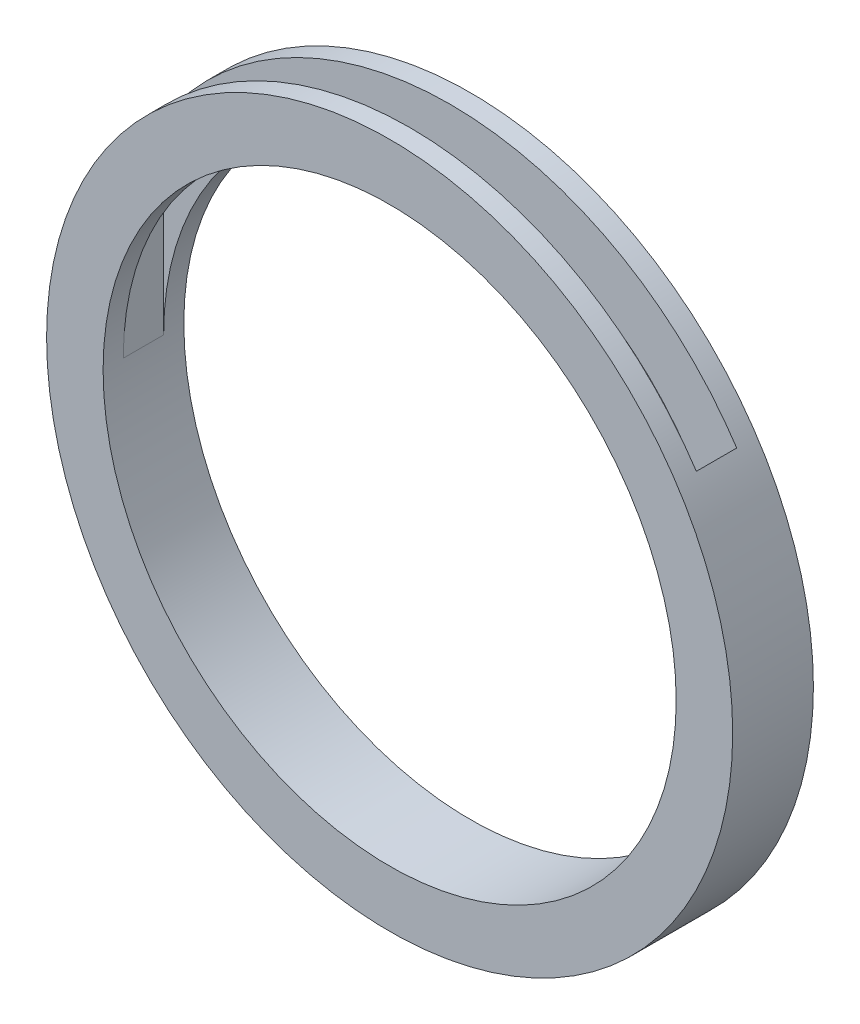
SolidWorks part; units mm, degrees
ref_plane "Front Plane" through (0, 0, 0) normal (0, 0, 1) x (1, 0, 0)
ref_plane "Top Plane" through (0, 0, 0) normal (0, 1, 0) x (1, 0, 0)
ref_plane "Right Plane" through (0, 0, 0) normal (1, 0, 0) x (0, 0, -1)
sketch "Sketch1" plane through (0, 0, 0) normal (0, 0, 1) x (1, 0, 0)
  circle A0 centre (0, 0) radius 21.59
  dimension "D1" = 43.18
extrude "Boss-Extrude1" add sketch "Sketch1" along normal blind 5.08
sketch "Sketch4" plane through (0, 0, 5.08) normal (0, 0, 1) x (1, 0, 0)
  circle A0 centre (0, 0) radius 18.034
  dimension "D1" = 36.068
extrude "Cut-Extrude1" cut sketch "Sketch4" against normal through all
sketch "Sketch5" plane through (0, 0, 0) normal (0, 1, 0) x (1, 0, 0)
  line L0 (-21.59, -2.54) -> (0, -2.54) construction
  line L1 (-21.59, 0) -> (-21.59, -5.08) construction
  line L3 (21.59, -3.81) -> (-21.59, -3.81)
  line L4 (21.59, -3.81) -> (21.59, -1.27)
  line L5 (21.59, -1.27) -> (-21.59, -1.27)
  line L6 (-21.59, -3.81) -> (-21.59, -1.27)
  line L7 (21.59, -3.81) -> (-21.59, -1.27) construction
  line L8 (21.59, -1.27) -> (-21.59, -3.81) construction
  dimension "D1" = 2.54
extrude "Cut-Extrude2" cut sketch "Sketch5" along normal through all
sketch "Sketch6" plane through (0, 0, 0) normal (0, 1, 0) x (1, 0, 0)
  line L1 (-21.59, -3.81) -> (-18.034, -3.81)
  line L2 (-21.59, -3.81) -> (-21.59, -1.27)
  line L3 (-21.59, -1.27) -> (-18.034, -1.27)
  line L4 (-18.034, -3.81) -> (-18.034, -1.27)
  line L5 (18.034, -1.27) -> (21.59, -1.27)
  line L6 (18.034, -1.27) -> (18.034, -3.81)
  line L7 (18.034, -3.81) -> (21.59, -3.81)
  line L8 (21.59, -1.27) -> (21.59, -3.81)
extrude "Boss-Extrude2" add sketch "Sketch6" along normal up to surface up to face at (21.59, 0, 0)
